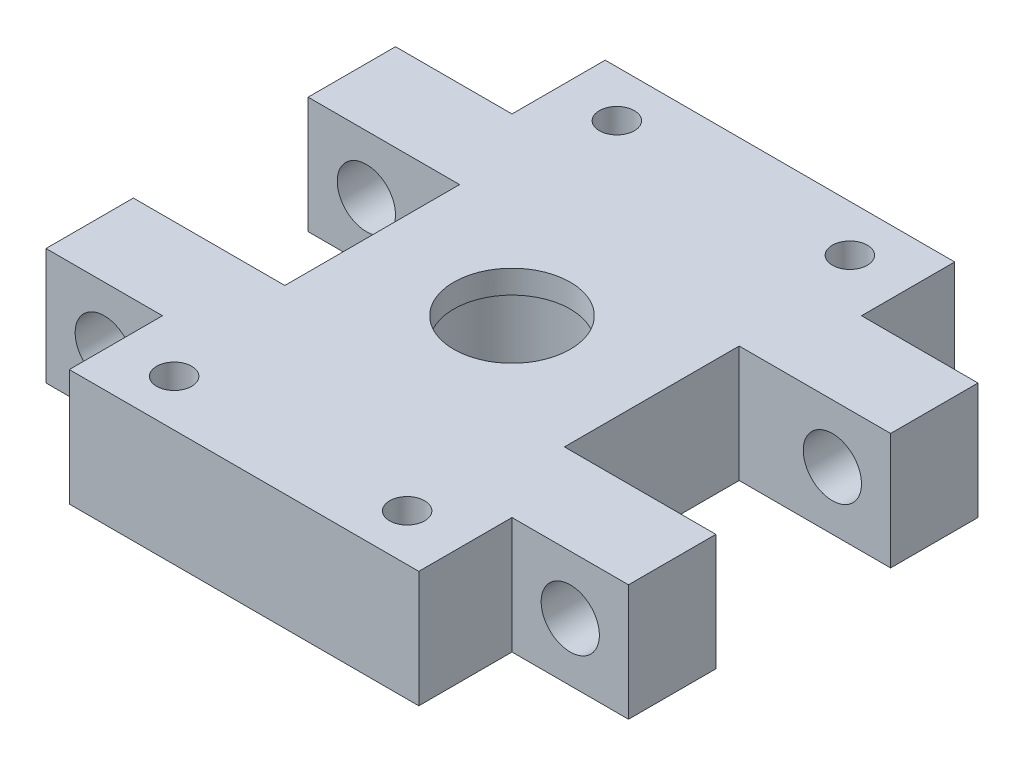
SolidWorks part; units mm, degrees
ref_plane "Front Plane" through (0, 0, 0) normal (0, 0, 1) x (1, 0, 0)
ref_plane "Top Plane" through (0, 0, 0) normal (0, 1, 0) x (1, 0, 0)
ref_plane "Right Plane" through (0, 0, 0) normal (1, 0, 0) x (0, 0, -1)
sketch "Sketch9" plane through (0, 0, 0) normal (0, 1, 0) x (1, 0, 0)
  line L0 (12, 7.5) -> (12, -7.5)
  line L1 (-25, 15) -> (-15, 15)
  line L2 (-25, 15) -> (-25, 7.5)
  line L3 (-25, -15) -> (-15, -15)
  line L4 (25, 15) -> (25, 7.5)
  line L5 (-25, 15) -> (25, -15) construction
  line L6 (-25, -15) -> (25, 15) construction
  line L7 (12, 7.5) -> (25, 7.5)
  line L8 (-37.5, 0) -> (37.5, 0) construction
  line L9 (0, 15) -> (0, -15) construction
  line L10 (12, -7.5) -> (25, -7.5)
  line L11 (-12, 7.5) -> (-25, 7.5)
  line L12 (-12, 7.5) -> (-12, -7.5)
  line L13 (-12, -7.5) -> (-25, -7.5)
  line L14 (-15, -15) -> (-15, -23)
  line L15 (-15, -23) -> (15, -23)
  line L16 (15, -23) -> (15, -15)
  line L17 (-15, 23) -> (15, 23)
  line L18 (15, 23) -> (15, 15)
  line L19 (-15, 15) -> (-15, 23)
  line L20 (15, 15) -> (25, 15)
  line L21 (15, -15) -> (25, -15)
  line L22 (-25, -7.5) -> (-25, -15)
  line L23 (25, -7.5) -> (25, -15)
  circle A0 centre (0, 0) radius 5
  point P0 (0, 0)
  dimension "D8" = 10
  dimension "D1" = 50
  dimension "D2" = 30
  dimension "D3" = 12
  dimension "D4" = 7.5
  dimension "D5" = 23
  dimension "D6" = 15
  dimension "D7" = 15
extrude "Boss-Extrude5" add sketch "Sketch9" along normal mid plane 10
sketch "Sketch10" plane through (0, 0, -15) normal (0, 0, -1) x (-1, 0, 0)
  line L0 (25, 5) -> (25, -5) construction
  line L1 (0, 5) -> (0, -5) construction
  line L2 (-15, 5) -> (15, 5) construction
  line L3 (-15, -5) -> (15, -5) construction
  circle A0 centre (20, 0) radius 2.5
  circle A1 centre (-20, 0) radius 2.5
  dimension "D1" = 5
  dimension "D2" = 5
extrude "Cut-Extrude5" cut sketch "Sketch10" against normal through all
sketch "Sketch11" plane through (0, -5, 0) normal (0, -1, 0) x (1, 0, 0)
  circle A0 centre (0, 0) radius 6
  dimension "D1" = 12
extrude "Cut-Extrude6" cut sketch "Sketch11" against normal blind 8
sketch "Sketch12" plane through (0, 5, 0) normal (0, 1, 0) x (1, 0, 0)
  line L0 (0, 23) -> (0, -23) construction
  line L1 (15, 23) -> (-15, 23) construction
  line L2 (-15, -23) -> (15, -23) construction
  line L3 (-12, 0) -> (12, 0) construction
  line L4 (-12, 7.5) -> (-12, -7.5) construction
  line L5 (12, -7.5) -> (12, 7.5) construction
  circle A0 centre (10, 19) radius 1.5
  circle A1 centre (-10, 19) radius 1.5
  circle A2 centre (10, -19) radius 1.5
  circle A3 centre (-10, -19) radius 1.5
  dimension "D2" = 3
  dimension "D1" = 10
  dimension "D3" = 19
extrude "Cut-Extrude7" cut sketch "Sketch12" against normal through all
